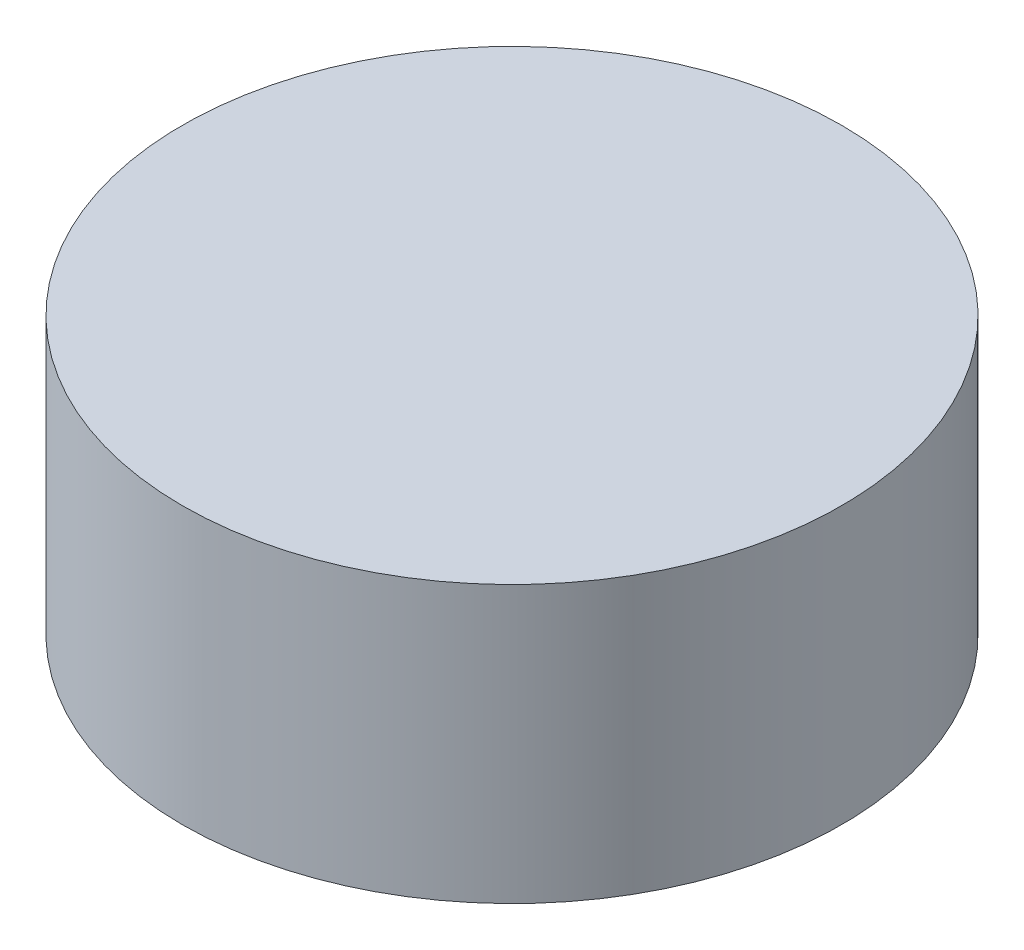
SolidWorks part; units mm, degrees
ref_plane "Front Plane" through (0, 0, 0) normal (0, 0, 1) x (1, 0, 0)
ref_plane "Top Plane" through (0, 0, 0) normal (0, 1, 0) x (1, 0, 0)
ref_plane "Right Plane" through (0, 0, 0) normal (1, 0, 0) x (0, 0, -1)
sketch "Sketch1" plane through (0, 0, 0) normal (1, 0, 0) x (0, 0, -1)
  line L0 (31.75, 0) -> (-31.75, 0) construction
  line L1 (-31.75, 0) -> (-43.201, 0) construction
  line L2 (-43.201, 0) -> (-43.201, 1.9844) construction
  line L3 (-43.201, 1.9844) -> (-33.676, 1.9844) construction
  line L4 (0, -1000) -> (0, 49000) construction
  line L5 (0, 33.7344) -> (0, 31.75) construction
  line L6 (-44.201, 0) -> (-44.201, 26.7344)
  line L7 (-34.201, 36.7344) -> (0, 36.7344)
  line L8 (0, 36.7344) -> (0, 38.7344)
  line L9 (0, 38.7344) -> (-46.201, 38.7344)
  line L10 (-46.201, 38.7344) -> (-46.201, 0)
  line L11 (-46.201, 0) -> (-44.201, 0)
  arc A0 (-31.75, 0) -> (0, 31.75) centre (0, 0) cw construction
  arc A1 (-33.676, 1.9844) -> (0, 33.7344) centre (0, 0) cw construction
  arc A2 (-33.7344, 0) -> (33.7344, 0) centre (0, 0) cw construction
  arc A3 (-31.75, 0) -> (31.75, 0) centre (0, 0) cw construction
  arc A4 (-44.201, 26.7344) -> (-34.201, 36.7344) centre (-34.201, 26.7344) cw
  point P4 (0, 0)
  dimension "D7" = 10
  dimension "D1" = 63.5
  dimension "D3" = 9.525
  dimension "D4" = 1.9844
  dimension "D5" = 2
  dimension "D6" = 2
  dimension "D8" = 1
  dimension "D9" = 3
  dimension "D2" = 1.9844
revolve "Revolve1" add sketch "Sketch1" angle 360 about L4
equation "\"D4@Sketch1\"=\"D2@Sketch1\""
